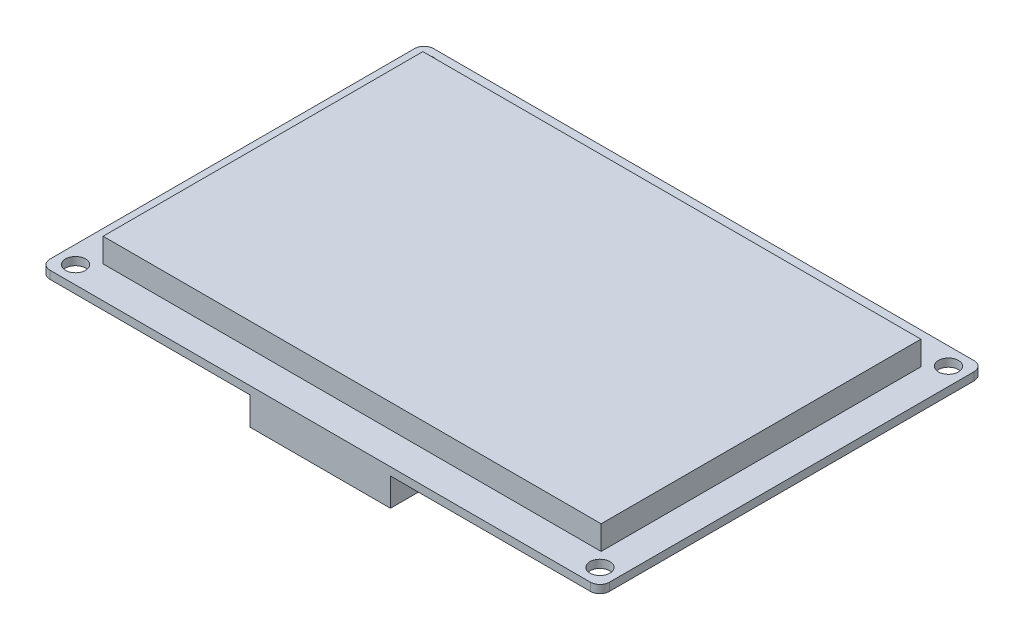
SolidWorks part; units mm, degrees
ref_plane "Front Plane" through (0, 0, 0) normal (0, 0, 1) x (1, 0, 0)
ref_plane "Top Plane" through (0, 0, 0) normal (0, 1, 0) x (1, 0, 0)
ref_plane "Right Plane" through (0, 0, 0) normal (1, 0, 0) x (0, 0, -1)
sketch "Sketch1" plane through (0, 0, 0) normal (0, 1, 0) x (1, 0, 0)
  line L0 (0, 0) -> (-35, 0) construction
  line L1 (-35, -24) -> (35, -24)
  line L2 (-35, -24) -> (-35, 24)
  line L3 (-35, 24) -> (35, 24)
  line L4 (35, -24) -> (35, 24)
  line L5 (-35, -24) -> (35, 24) construction
  line L6 (-35, 24) -> (35, -24) construction
  line L7 (0, 0) -> (0, 24) construction
  circle A0 centre (-32.8, 21.8) radius 1.25
  circle A1 centre (-32.8, -21.8) radius 1.25
  circle A2 centre (32.8, -21.8) radius 1.25
  circle A3 centre (32.8, 21.8) radius 1.25
  point P0 (0, 0)
  dimension "D3" = 2.5
  dimension "D1" = 70
  dimension "D2" = 48
  dimension "D4" = 2.2
  dimension "D5" = 2.2
extrude "Boss-Extrude1" add sketch "Sketch1" along normal blind 1
sketch "Sketch2" plane through (0, 1, 0) normal (0, 1, 0) x (1, 0, 0)
  line L1 (-31.15, -20) -> (31.15, -20)
  line L2 (-31.15, -20) -> (-31.15, 20)
  line L3 (-31.15, 20) -> (31.15, 20)
  line L4 (31.15, -20) -> (31.15, 20)
  line L5 (-31.15, -20) -> (31.15, 20) construction
  line L6 (-31.15, 20) -> (31.15, -20) construction
  point P0 (0, 0)
  point P5 (0, 0)
  dimension "D1" = 40
  dimension "D2" = 62.3
extrude "Boss-Extrude2" add sketch "Sketch2" along normal blind 3
sketch "Sketch4" plane through (0, 0, 0) normal (0, -1, 0) x (1, 0, 0)
  line L0 (-35, 24) -> (35, 24) construction
  line L1 (-8.8, -7) -> (8.8, -7)
  line L2 (-8.8, -7) -> (-8.8, 24)
  line L3 (-8.8, 24) -> (8.8, 24)
  line L4 (8.8, -7) -> (8.8, 24)
  line L5 (-8.8, -7) -> (8.8, 24) construction
  line L6 (-8.8, 24) -> (8.8, -7) construction
  line L7 (0, 8.5) -> (0, -0.5369) construction
  point P0 (0, 8.5)
  dimension "D1" = 17.6
  dimension "D2" = 31
extrude "Boss-Extrude3" add sketch "Sketch4" along normal blind 3.5
fillet "Fillet1" radius 1.2 4 edges at (-35, 0.5, 24) (-35, 0.5, -24) (35, 0.5, -24) (35, 0.5, 24)
